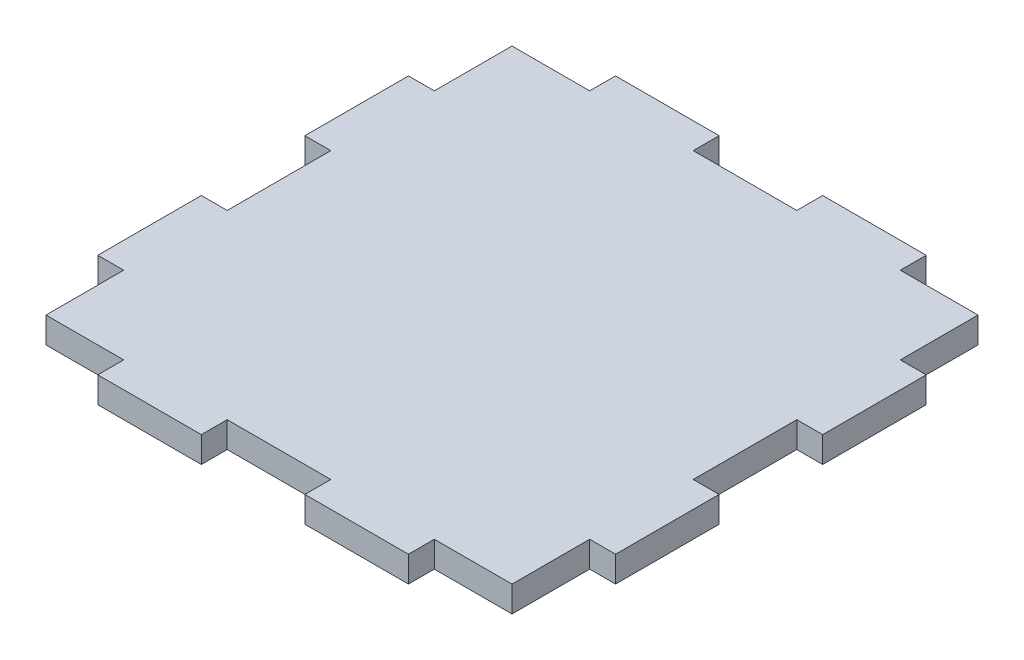
SolidWorks part; units mm, degrees
ref_plane "Front Plane" through (0, 0, 0) normal (0, 0, 1) x (1, 0, 0)
ref_plane "Top Plane" through (0, 0, 0) normal (0, 1, 0) x (1, 0, 0)
ref_plane "Right Plane" through (0, 0, 0) normal (1, 0, 0) x (0, 0, -1)
sketch "Sketch1" plane through (0, 0, 0) normal (0, 1, 0) x (1, 0, 0)
  line L1 (-186.2722, 187.3213) -> (4.2278, 187.3213)
  line L2 (-186.2722, 187.3213) -> (-186.2722, -3.1787)
  line L3 (-186.2722, -3.1787) -> (4.2278, -3.1787)
  line L4 (4.2278, 187.3213) -> (4.2278, -3.1787)
  dimension "D1" = 190.5
  dimension "D2" = 190.5
extrude "Boss-Extrude1" add sketch "Sketch1" along normal blind 9.525
sketch "Sketch2" plane through (0, 9.525, 0) normal (0, 1, 0) x (1, 0, 0)
  line L0 (-186.2722, -3.1787) -> (4.2278, -3.1787) construction
  line L1 (-5.2972, -3.1787) -> (4.2278, -3.1787)
  line L2 (-5.2972, -3.1787) -> (-5.2972, 34.9213)
  line L3 (-5.2972, 34.9213) -> (4.2278, 34.9213)
  line L4 (4.2278, -3.1787) -> (4.2278, 34.9213)
  line L5 (4.2278, -3.1787) -> (4.2278, 187.3213) construction
  dimension "D1" = 38.1
  dimension "D2" = 9.525
extrude "Cut-Extrude1" cut sketch "Sketch2" against normal blind 9.525
sketch "Sketch3" plane through (0, 9.525, 0) normal (0, 1, 0) x (1, 0, 0)
  line L0 (4.2278, 34.9213) -> (4.2278, 187.3213) construction
  line L1 (4.2278, 73.0213) -> (-5.2972, 73.0213)
  line L2 (4.2278, 73.0213) -> (4.2278, 111.1213)
  line L3 (4.2278, 111.1213) -> (-5.2972, 111.1213)
  line L4 (-5.2972, 73.0213) -> (-5.2972, 111.1213)
  dimension "D1" = 9.525
  dimension "D2" = 38.1
  dimension "D3" = 38.1
extrude "Cut-Extrude2" cut sketch "Sketch3" against normal blind 9.525
sketch "Sketch4" plane through (0, 9.525, 0) normal (0, 1, 0) x (1, 0, 0)
  line L0 (4.2278, 111.1213) -> (4.2278, 187.3213) construction
  line L1 (4.2278, 149.2213) -> (-5.2972, 149.2213)
  line L2 (4.2278, 149.2213) -> (4.2278, 187.3213)
  line L3 (4.2278, 187.3213) -> (-5.2972, 187.3213)
  line L4 (-5.2972, 149.2213) -> (-5.2972, 187.3213)
  line L5 (4.2278, 187.3213) -> (-186.2722, 187.3213) construction
  dimension "D1" = 9.525
  dimension "D2" = 38.1
extrude "Cut-Extrude3" cut sketch "Sketch4" against normal blind 9.525
sketch "Sketch5" plane through (0, 0, 0) normal (0, -1, 0) x (1, 0, 0)
  line L0 (-186.2722, 3.1787) -> (-5.2972, 3.1787) construction
  line L1 (-176.7472, 3.1787) -> (-186.2722, 3.1787)
  line L2 (-176.7472, 3.1787) -> (-176.7472, -34.9213)
  line L3 (-176.7472, -34.9213) -> (-186.2722, -34.9213)
  line L4 (-186.2722, 3.1787) -> (-186.2722, -34.9213)
  line L5 (-186.2722, -187.3213) -> (-186.2722, 3.1787) construction
  dimension "D1" = 9.525
  dimension "D2" = 38.1
extrude "Cut-Extrude4" cut sketch "Sketch5" against normal blind 9.525
sketch "Sketch6" plane through (0, 0, 0) normal (0, -1, 0) x (1, 0, 0)
  line L0 (-186.2722, -187.3213) -> (-186.2722, -34.9213) construction
  line L1 (-186.2722, -73.0213) -> (-176.7472, -73.0213)
  line L2 (-186.2722, -73.0213) -> (-186.2722, -111.1213)
  line L3 (-186.2722, -111.1213) -> (-176.7472, -111.1213)
  line L4 (-176.7472, -73.0213) -> (-176.7472, -111.1213)
  dimension "D1" = 38.1
  dimension "D2" = 9.525
  dimension "D3" = 38.1
extrude "Cut-Extrude5" cut sketch "Sketch6" against normal blind 9.525
sketch "Sketch7" plane through (0, 0, 0) normal (0, -1, 0) x (1, 0, 0)
  line L0 (-186.2722, -187.3213) -> (-186.2722, -111.1213) construction
  line L1 (-186.2722, -149.2213) -> (-176.7472, -149.2213)
  line L2 (-186.2722, -149.2213) -> (-186.2722, -187.3213)
  line L3 (-186.2722, -187.3213) -> (-176.7472, -187.3213)
  line L4 (-176.7472, -149.2213) -> (-176.7472, -187.3213)
  line L5 (-5.2972, -187.3213) -> (-186.2722, -187.3213) construction
  dimension "D1" = 9.525
extrude "Cut-Extrude6" cut sketch "Sketch7" against normal blind 9.525
sketch "Sketch8" plane through (0, 0, 0) normal (0, -1, 0) x (1, 0, 0)
  line L0 (-5.2972, -187.3213) -> (-5.2972, -149.2213) construction
  line L1 (-5.2972, -177.7963) -> (-33.8722, -177.7963)
  line L2 (-5.2972, -177.7963) -> (-5.2972, -187.3213)
  line L3 (-5.2972, -187.3213) -> (-33.8722, -187.3213)
  line L4 (-33.8722, -177.7963) -> (-33.8722, -187.3213)
  line L5 (-5.2972, -187.3213) -> (-176.7472, -187.3213) construction
  dimension "D1" = 28.575
  dimension "D2" = 9.525
extrude "Cut-Extrude7" cut sketch "Sketch8" against normal blind 9.525
sketch "Sketch9" plane through (0, 0, 0) normal (0, -1, 0) x (1, 0, 0)
  line L0 (-33.8722, -187.3213) -> (-176.7472, -187.3213) construction
  line L1 (-71.9722, -187.3213) -> (-110.0722, -187.3213)
  line L2 (-71.9722, -187.3213) -> (-71.9722, -177.7963)
  line L3 (-71.9722, -177.7963) -> (-110.0722, -177.7963)
  line L4 (-110.0722, -187.3213) -> (-110.0722, -177.7963)
  dimension "D1" = 38.1
  dimension "D2" = 38.1
  dimension "D3" = 9.525
extrude "Cut-Extrude8" cut sketch "Sketch9" against normal blind 9.525
sketch "Sketch10" plane through (0, 0, 0) normal (0, -1, 0) x (1, 0, 0)
  line L0 (-110.0722, -187.3213) -> (-176.7472, -187.3213) construction
  line L1 (-148.1722, -187.3213) -> (-176.7472, -187.3213)
  line L2 (-148.1722, -187.3213) -> (-148.1722, -177.7963)
  line L3 (-148.1722, -177.7963) -> (-176.7472, -177.7963)
  line L4 (-176.7472, -187.3213) -> (-176.7472, -177.7963)
  line L5 (-176.7472, -187.3213) -> (-176.7472, -149.2213) construction
  dimension "D1" = 38.1
  dimension "D2" = 9.525
extrude "Cut-Extrude9" cut sketch "Sketch10" against normal blind 9.525
sketch "Sketch11" plane through (0, 0, 0) normal (0, -1, 0) x (-1, 0, 0)
  line L0 (176.7472, 34.9213) -> (176.7472, -3.1787) construction
  line L1 (176.7472, 6.3463) -> (148.1722, 6.3463)
  line L2 (176.7472, 6.3463) -> (176.7472, -3.1787)
  line L3 (176.7472, -3.1787) -> (148.1722, -3.1787)
  line L4 (148.1722, 6.3463) -> (148.1722, -3.1787)
  line L5 (176.7472, -3.1787) -> (5.2972, -3.1787) construction
  dimension "D1" = 28.575
  dimension "D2" = 9.525
extrude "Cut-Extrude11" cut sketch "Sketch11" against normal blind 9.525
sketch "Sketch12" plane through (0, 0, 0) normal (0, -1, 0) x (1, 0, 0)
  line L0 (-148.1722, 3.1787) -> (-5.2972, 3.1787) construction
  line L1 (-110.0722, 3.1787) -> (-71.9722, 3.1787)
  line L2 (-110.0722, 3.1787) -> (-110.0722, -6.3463)
  line L3 (-110.0722, -6.3463) -> (-71.9722, -6.3463)
  line L4 (-71.9722, 3.1787) -> (-71.9722, -6.3463)
  line L5 (-148.1722, -6.3463) -> (-148.1722, 3.1787) construction
  dimension "D1" = 38.1
  dimension "D2" = 9.525
  dimension "D3" = 38.1
extrude "Cut-Extrude12" cut sketch "Sketch12" against normal blind 9.525
sketch "Sketch14" plane through (0, 0, 0) normal (0, -1, 0) x (-1, 0, 0)
  line L0 (71.9722, -3.1787) -> (5.2972, -3.1787) construction
  line L1 (33.8722, -3.1787) -> (5.2972, -3.1787)
  line L2 (33.8722, -3.1787) -> (33.8722, 6.3463)
  line L3 (33.8722, 6.3463) -> (5.2972, 6.3463)
  line L4 (5.2972, -3.1787) -> (5.2972, 6.3463)
  line L5 (5.2972, 34.9213) -> (5.2972, -3.1787) construction
  line L6 (71.9722, 6.3463) -> (71.9722, -3.1787) construction
  dimension "D1" = 38.1
  dimension "D2" = 9.525
extrude "Cut-Extrude13" cut sketch "Sketch14" against normal blind 9.525
